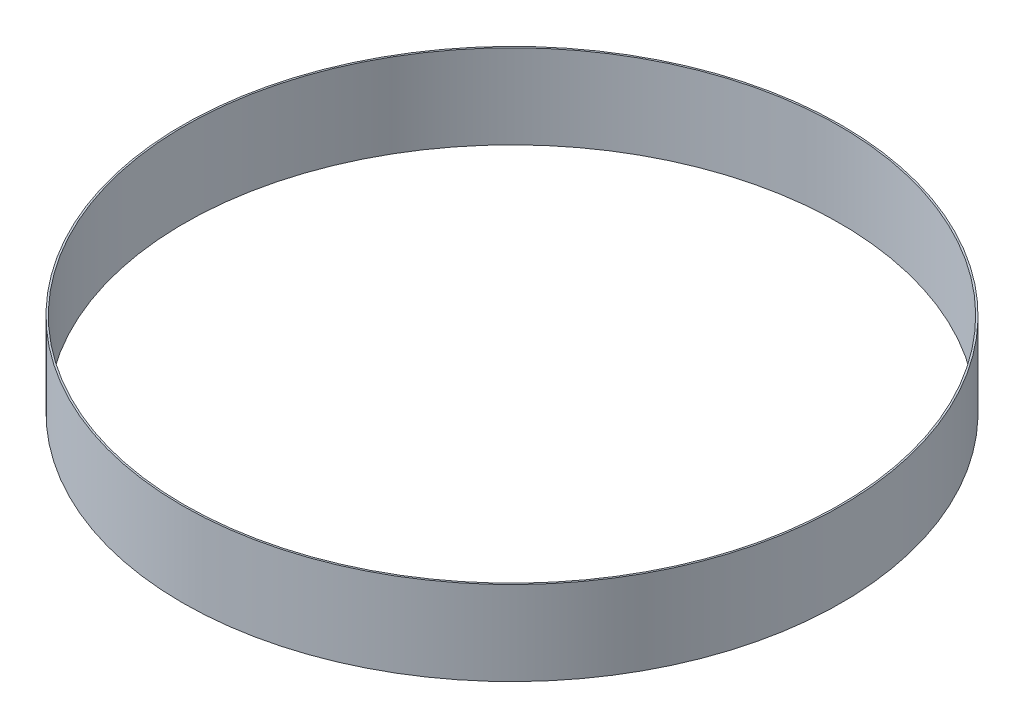
SolidWorks part; units mm, degrees
ref_plane "Front Plane" through (0, 0, 0) normal (0, 0, 1) x (1, 0, 0)
ref_plane "Top Plane" through (0, 0, 0) normal (0, 1, 0) x (1, 0, 0)
ref_plane "Right Plane" through (0, 0, 0) normal (1, 0, 0) x (0, 0, -1)
sketch "Sketch1" plane through (0, 0, 0) normal (0, 1, 0) x (1, 0, 0)
  circle A0 centre (0, 0) radius 19.5
  circle A1 centre (0, 0) radius 19.6
  dimension "D1" = 39
  dimension "D2" = 0.1
extrude "Boss-Extrude1" add sketch "Sketch1" along normal blind 5
